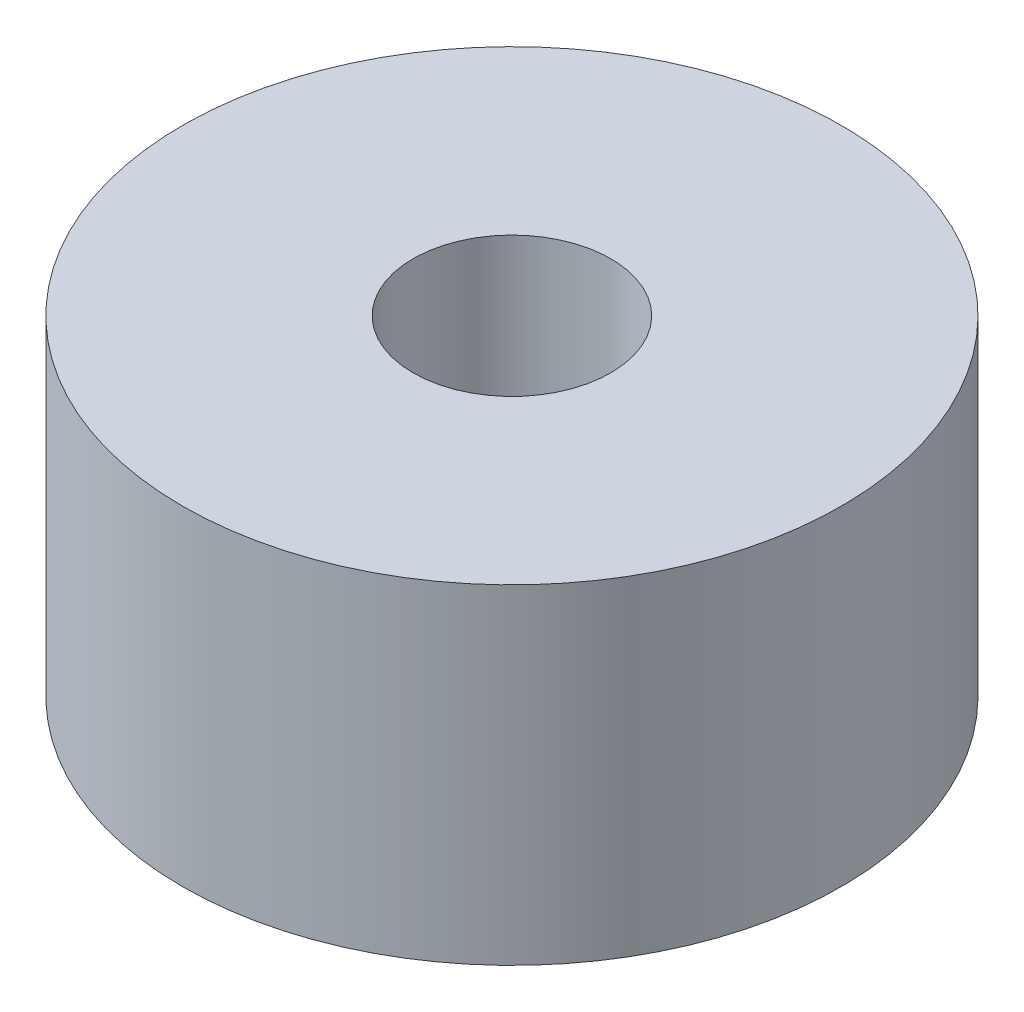
SolidWorks part; units mm, degrees
material "AISI 316 Stainless Steel Sheet (SS)"
ref_plane "Front Plane" through (0, 0, 0) normal (0, 0, 1) x (1, 0, 0)
ref_plane "Top Plane" through (0, 0, 0) normal (0, 1, 0) x (1, 0, 0)
ref_plane "Right Plane" through (0, 0, 0) normal (1, 0, 0) x (0, 0, -1)
sketch "Sketch1" plane through (0, 0, 0) normal (1, 0, 0) x (0, 0, -1)
  line L0 (0, 96.9717) -> (0, -67.9211) construction
  line L1 (-100, 50) -> (-100, -50)
  line L2 (-100, 50) -> (-30, 50)
  line L3 (-30, 50) -> (-30, -50)
  line L4 (-30, -50) -> (-100, -50)
  point P5 (-100, 0)
  dimension "D1" = 100
  dimension "D2" = 30
  dimension "D3" = 100
revolve "Revolve1" add sketch "Sketch1" angle 360 about L0
